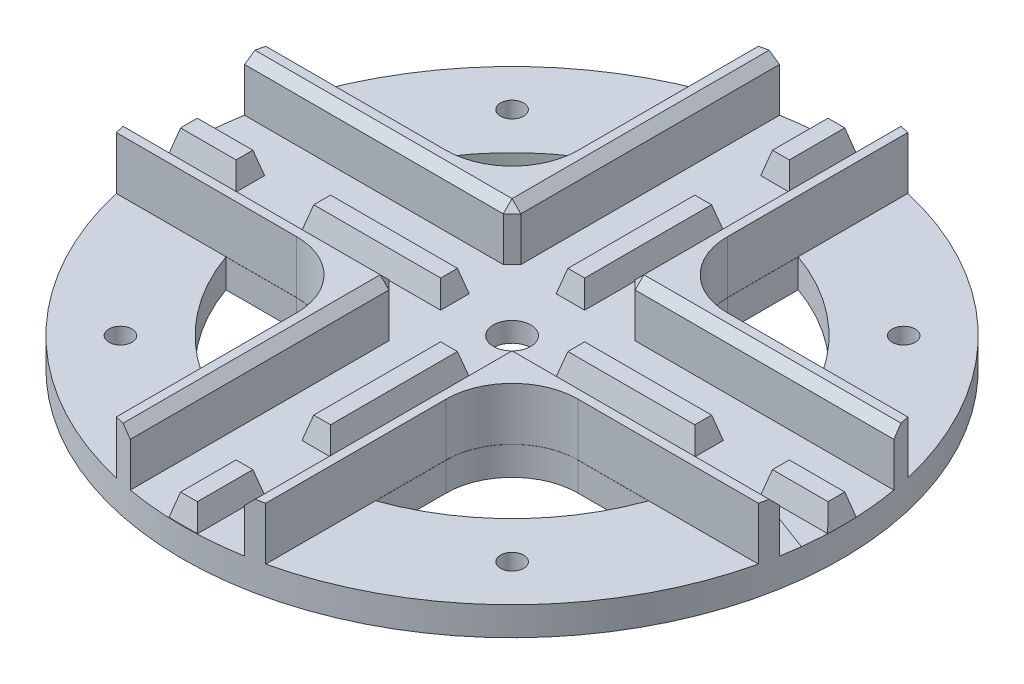
SolidWorks part; units mm, degrees
ref_plane "Front Plane" through (0, 0, 0) normal (0, 0, 1) x (1, 0, 0)
ref_plane "Top Plane" through (0, 0, 0) normal (0, 1, 0) x (1, 0, 0)
ref_plane "Right Plane" through (0, 0, 0) normal (1, 0, 0) x (0, 0, -1)
sketch "Sketch1" plane through (0, 0, 0) normal (0, 1, 0) x (1, 0, 0)
  circle A0 centre (0, 0) radius 75
  circle A1 centre (0, 0) radius 4.25
  dimension "D1" = 150
  dimension "D2" = 8.5
extrude "Boss-Extrude1" add sketch "Sketch1" along normal blind 6.5
sketch "Sketch2" plane through (0, 6.5, 0) normal (0, 1, 0) x (1, 0, 0)
  line L32 (-13, -13) -> (-73.8647, -13)
  line L33 (-13, -13) -> (-13, -73.8647)
  line L47 (-17, -32) -> (-17, -73.0479)
  line L48 (-32, -17) -> (-73.0479, -17)
  line L49 (0, 0) -> (-19.05, 0) construction
  line L50 (0, 0) -> (0, 16.1949) construction
  line L51 (-32, 17) -> (-73.0479, 17)
  line L52 (-13, 13) -> (-73.8647, 13)
  line L53 (-13, 13) -> (-13, 73.8647)
  line L54 (-17, 32) -> (-17, 73.0479)
  line L56 (17, 32) -> (17, 73.0479)
  line L57 (13, 13) -> (13, 73.8647)
  line L58 (13, 13) -> (73.8647, 13)
  line L59 (32, 17) -> (73.0479, 17)
  line L60 (32, -17) -> (73.0479, -17)
  line L61 (13, -13) -> (73.8647, -13)
  line L62 (13, -13) -> (13, -73.8647)
  line L63 (17, -32) -> (17, -73.0479)
  arc A5 (-17, -73.0479) -> (-13, -73.8647) centre (0, 0) ccw
  arc A6 (-73.8647, -13) -> (-73.0479, -17) centre (0, 0) ccw
  arc A7 (-73.8647, 13) -> (-73.0479, 17) centre (0, 0) cw
  arc A8 (-17, 73.0479) -> (-13, 73.8647) centre (0, 0) cw
  arc A9 (17, 73.0479) -> (13, 73.8647) centre (0, 0) ccw
  arc A10 (73.8647, 13) -> (73.0479, 17) centre (0, 0) ccw
  arc A11 (73.8647, -13) -> (73.0479, -17) centre (0, 0) cw
  arc A12 (17, -73.0479) -> (13, -73.8647) centre (0, 0) cw
  arc A13 (32, -17) -> (17, -32) centre (32, -32) ccw
  arc A14 (17, 32) -> (32, 17) centre (32, 32) ccw
  arc A15 (-32, 17) -> (-17, 32) centre (-32, 32) ccw
  arc A16 (-17, -32) -> (-32, -17) centre (-32, -32) ccw
  point P29 (17, -17)
  point P32 (17, 17)
  point P35 (-17, 17)
  point P38 (-17, -17)
  dimension "D5" = 15
  dimension "D1" = 13
  dimension "D2" = 13
  dimension "D3" = 4
  dimension "D4" = 4
extrude "Boss-Extrude2" add sketch "Sketch2" along normal blind 12
chamfer "Chamfer1" distance 2 angle 45 12 edges at (13, 12.5, -13) (43.4324, 18.5, -13) (13, 18.5, -43.4324) (-13, 12.5, -13) (-13, 18.5, -43.4324) (-43.4324, 18.5, -13) (-13, 12.5, 13) (-43.4324, 18.5, 13) (-13, 18.5, 43.4324) (13, 12.5, 13) (13, 18.5, 43.4324) (43.4324, 18.5, 13)
sketch "Sketch3" plane through (0, 6.5, 0) normal (0, 1, 0) x (1, 0, 0)
  line L0 (32.0104, -17.0271) -> (48.0737, -17.0271)
  line L1 (17.0271, -32.0104) -> (17.0271, -48.0737)
  line L2 (0, 0) -> (0, -22.59) construction
  line L3 (0, 0) -> (-26.3767, 0) construction
  line L4 (-17.0271, -32.0104) -> (-17.0271, -48.0737)
  line L5 (-32.0104, -17.0271) -> (-48.0737, -17.0271)
  line L6 (17.0271, 32.0104) -> (17.0271, 48.0737)
  line L7 (32.0104, 17.0271) -> (48.0737, 17.0271)
  line L8 (-32.0104, 17.0271) -> (-48.0737, 17.0271)
  line L9 (-17.0271, 32.0104) -> (-17.0271, 48.0737)
  arc A0 (17.0271, -48.0737) -> (48.0737, -17.0271) centre (0, 0) ccw
  arc A1 (32.0104, -17.0271) -> (17.0271, -32.0104) centre (32.0104, -32.0104) ccw
  arc A2 (-32.0104, -17.0271) -> (-17.0271, -32.0104) centre (-32.0104, -32.0104) cw
  arc A3 (-17.0271, -48.0737) -> (-48.0737, -17.0271) centre (0, 0) cw
  arc A4 (32.0104, 17.0271) -> (17.0271, 32.0104) centre (32.0104, 32.0104) cw
  arc A5 (17.0271, 48.0737) -> (48.0737, 17.0271) centre (0, 0) cw
  arc A6 (-17.0271, 48.0737) -> (-48.0737, 17.0271) centre (0, 0) ccw
  arc A7 (-32.0104, 17.0271) -> (-17.0271, 32.0104) centre (-32.0104, 32.0104) ccw
  dimension "D1" = 102
extrude "Cut-Extrude1" cut sketch "Sketch3" against normal up to surface (6.5 mm away) up to face at (0, 0, 75)
sketch "Sketch4" plane through (0, 6.5, 0) normal (0, 1, 0) x (1, 0, 0)
  line L0 (0, 0) -> (-44.5477, 44.5477) construction
  line L1 (0, 0) -> (-44.5477, -44.5477) construction
  line L2 (0, 0) -> (44.5477, -44.5477) construction
  line L3 (0, 0) -> (44.5477, 44.5477) construction
  circle A0 centre (0, 0) radius 63 construction
  circle A1 centre (44.5477, -44.5477) radius 2.625
  circle A2 centre (-44.5477, -44.5477) radius 2.625
  circle A3 centre (44.5477, 44.5477) radius 2.625
  circle A4 centre (-44.5477, 44.5477) radius 2.625
  dimension "D1" = 126
  dimension "D2" = 5.25
  dimension "D3" = 5.25
  dimension "D4" = 5.25
  dimension "D5" = 5.25
extrude "Cut-Extrude2" cut sketch "Sketch4" against normal up to surface (6.5 mm away) up to face at (-28.6368, 0, 28.6368)
sketch "Sketch5" plane through (0, 6.5, 0) normal (0, 1, 0) x (1, 0, 0)
  line L0 (-44.6839, 3.3862) -> (-44.6839, -3.1138)
  line L2 (-3.25, -74.7933) -> (-3.25, -59.5477)
  line L4 (3.25, -74.7933) -> (3.25, -59.5477)
  line L6 (0, 0.1362) -> (28.5092, 0.1362) construction
  line L7 (-3.25, -44.5477) -> (3.25, -44.5477)
  line L9 (-3.25, -13) -> (3.25, -13)
  line L11 (-3.25, -59.5477) -> (3.25, -59.5477)
  line L12 (-3.25, -44.5477) -> (-3.25, -13)
  line L15 (3.25, -44.5477) -> (3.25, -13)
  line L17 (0, 0.1362) -> (0, 27.1943) construction
  line L18 (-44.6839, -3.1138) -> (-13.1362, -3.1138)
  line L19 (-13.1362, 3.3862) -> (-13.1362, -3.1138)
  line L20 (-44.6839, 3.3862) -> (-13.1362, 3.3862)
  line L21 (-74.9296, 3.3862) -> (-59.6839, 3.3862)
  line L22 (-59.6839, 3.3862) -> (-59.6839, -3.1138)
  line L23 (-74.9296, -3.1138) -> (-59.6839, -3.1138)
  line L24 (3.25, 44.8201) -> (-3.25, 44.8201)
  line L25 (-3.25, 44.8201) -> (-3.25, 13.2724)
  line L26 (3.25, 13.2724) -> (-3.25, 13.2724)
  line L27 (3.25, 44.8201) -> (3.25, 13.2724)
  line L28 (3.25, 75.0658) -> (3.25, 59.8201)
  line L29 (3.25, 59.8201) -> (-3.25, 59.8201)
  line L30 (-3.25, 75.0658) -> (-3.25, 59.8201)
  line L31 (44.6839, -3.1138) -> (44.6839, 3.3862)
  line L32 (44.6839, 3.3862) -> (13.1362, 3.3862)
  line L33 (13.1362, -3.1138) -> (13.1362, 3.3862)
  line L34 (44.6839, -3.1138) -> (13.1362, -3.1138)
  line L35 (74.9296, -3.1138) -> (59.6839, -3.1138)
  line L36 (59.6839, -3.1138) -> (59.6839, 3.3862)
  line L37 (74.9296, 3.3862) -> (59.6839, 3.3862)
  arc A0 (-3.25, -74.7933) -> (3.25, -74.7933) centre (0, 0.1362) ccw
  arc A1 (-74.9296, 3.3862) -> (-74.9296, -3.1138) centre (0, 0.1362) ccw
  arc A2 (3.25, 75.0658) -> (-3.25, 75.0658) centre (0, 0.1362) ccw
  arc A3 (74.9296, -3.1138) -> (74.9296, 3.3862) centre (0, 0.1362) ccw
  point P0 (0, 0)
  dimension "D1" = 15
  dimension "D3" = 6.5
  dimension "D4" = 3.25
  dimension "D2" = 4
extrude "Boss-Extrude3" add sketch "Sketch5" along normal blind 5 draft 15
sketch "Sketch6" plane through (0, 0, 0) normal (0, -1, 0) x (1, 0, 0)
  circle A0 centre (0, 0) radius 12.125
  dimension "D1" = 24.25
extrude "Cut-Extrude3" cut sketch "Sketch6" against normal blind 2
